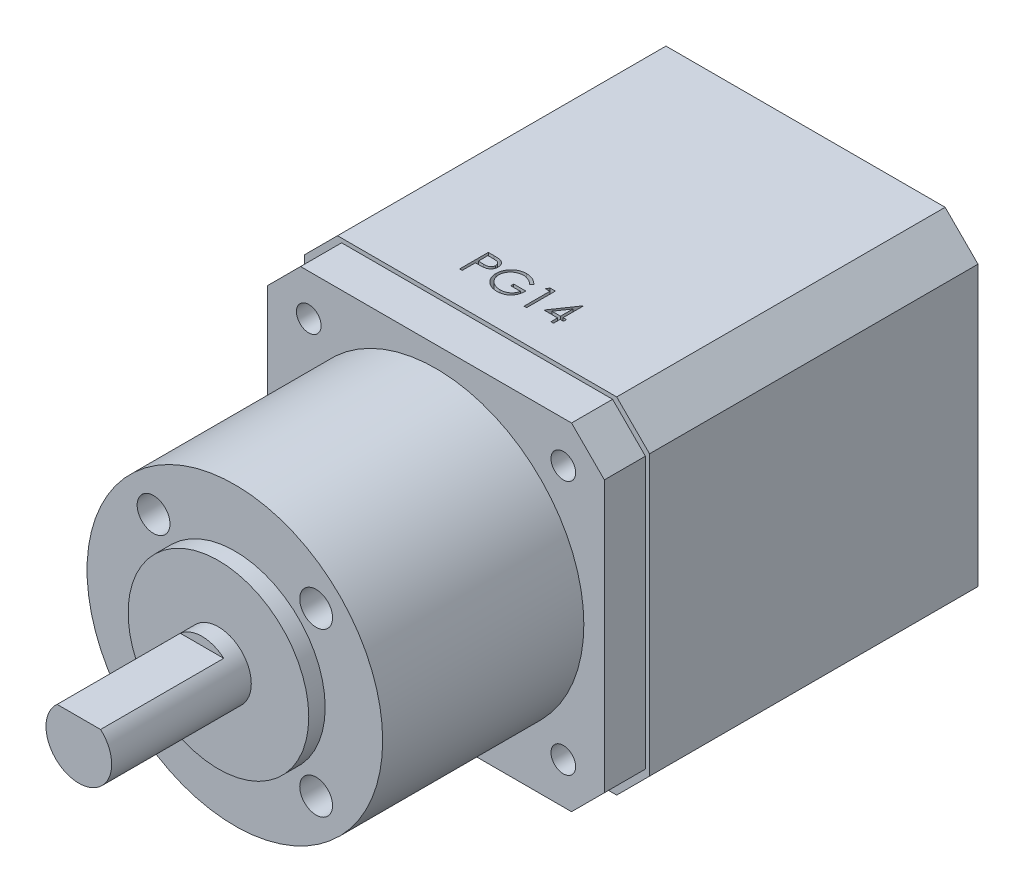
SolidWorks part; units mm, degrees
material "M1"
ref_plane "Front Plane" through (0, 0, 0) normal (0, 0, 1) x (1, 0, 0)
ref_plane "Top Plane" through (0, 0, 0) normal (0, 1, 0) x (1, 0, 0)
ref_plane "Right Plane" through (0, 0, 0) normal (1, 0, 0) x (0, 0, -1)
sketch "Sketch1" plane through (0, 0, 0) normal (0, 0, 1) x (1, 0, 0)
  line L1 (-21, -21) -> (21, -21)
  line L2 (-21, -21) -> (-21, 21)
  line L3 (-21, 21) -> (21, 21)
  line L4 (21, -21) -> (21, 21)
  line L5 (-21, -21) -> (21, 21) construction
  line L6 (-21, 21) -> (21, -21) construction
  point P0 (0, 0)
  dimension "D1" = 42
extrude "Boss-Extrude1" add sketch "Sketch1" along normal blind 40
sketch "Sketch2" plane through (0, 0, 40) normal (0, 0, 1) x (1, 0, 0)
  line L8 (20.5, -20.5) -> (20.5, 20.5)
  line L9 (20.5, 20.5) -> (-20.5, 20.5)
  line L10 (-20.5, 20.5) -> (-20.5, -20.5)
  line L11 (-20.5, -20.5) -> (20.5, -20.5)
  line L12 (20.5, -20.5) -> (20.5, 20.5)
  line L13 (20.5, 20.5) -> (-20.5, 20.5)
  line L14 (-20.5, 20.5) -> (-20.5, -20.5)
  line L15 (-20.5, -20.5) -> (20.5, -20.5)
  dimension "D1" = 0.5
extrude "Boss-Extrude2" add sketch "Sketch2" along normal blind 5
sketch "Sketch3" plane through (0, 0, 45) normal (0, 0, 1) x (1, 0, 0)
  circle A0 centre (0, 0) radius 18
  dimension "D1" = 36
extrude "Boss-Extrude3" add sketch "Sketch3" along normal blind 24.5
sketch "Sketch4" plane through (0, 0, 69.5) normal (0, 0, 1) x (1, 0, 0)
  circle A0 centre (0, 0) radius 11
  dimension "D1" = 22
extrude "Boss-Extrude4" add sketch "Sketch4" along normal blind 2
sketch "Sketch5" plane through (0, 0, 71.5) normal (0, 0, 1) x (1, 0, 0)
  circle A0 centre (0, 0) radius 4
  dimension "D1" = 8
extrude "Boss-Extrude5" add sketch "Sketch5" along normal blind 17
chamfer "Chamfer1" distance 4 angle 45 8 edges at (-21, 21, 20) (-20.5, 20.5, 42.5) (-21, -21, 20) (-20.5, -20.5, 42.5) (21, -21, 20) (20.5, -20.5, 42.5) (21, 21, 20) (20.5, 20.5, 42.5)
sketch "Sketch6" plane through (0, 0, 45) normal (0, 0, 1) x (1, 0, 0)
  line L1 (-15.5, -15.5) -> (15.5, -15.5) construction
  line L2 (-15.5, -15.5) -> (-15.5, 15.5) construction
  line L3 (-15.5, 15.5) -> (15.5, 15.5) construction
  line L4 (15.5, -15.5) -> (15.5, 15.5) construction
  line L5 (-15.5, -15.5) -> (15.5, 15.5) construction
  line L6 (-15.5, 15.5) -> (15.5, -15.5) construction
  circle A0 centre (15.5, 15.5) radius 1.5
  point P0 (0, 0)
  dimension "D2" = 3
  dimension "D1" = 31
extrude "Cut-Extrude1" cut sketch "Sketch6" against normal blind 8
pattern_circular "CirPattern1" count 4 over 360 about axis through (0, 0, 0) along (0, 0, 1) of "Cut-Extrude1"
sketch "Sketch7" plane through (0, 0, 69.5) normal (0, 0, 1) x (1, 0, 0)
  line L1 (-9.8995, -9.8995) -> (9.8995, -9.8995) construction
  line L2 (-9.8995, -9.8995) -> (-9.8995, 9.8995) construction
  line L3 (-9.8995, 9.8995) -> (9.8995, 9.8995) construction
  line L4 (9.8995, -9.8995) -> (9.8995, 9.8995) construction
  line L5 (-9.8995, -9.8995) -> (9.8995, 9.8995) construction
  line L6 (-9.8995, 9.8995) -> (9.8995, -9.8995) construction
  circle A0 centre (0, 0) radius 14 construction
  circle A1 centre (9.8995, 9.8995) radius 2
  dimension "D1" = 28
  dimension "D2" = 4
extrude "Cut-Extrude2" cut sketch "Sketch7" against normal blind 8
pattern_circular "CirPattern2" count 4 over 360 about axis through (0, 0, 0) along (0, 0, 1) of "Cut-Extrude2"
sketch "Sketch8" plane through (0, 0, 88.5) normal (0, 0, 1) x (1, 0, 0)
  line L0 (0, -4) -> (0, 3) construction
  line L1 (0, 3) -> (2.6458, 3) construction
  line L2 (2.6458, 3) -> (-2.6458, 3)
  circle A0 centre (0, 0) radius 4 construction
  circle A1 centre (0, 0) radius 4 construction
  arc A2 (-2.6458, 3) -> (2.6458, 3) centre (0, 0) cw
  dimension "D1" = 7
extrude "Cut-Extrude3" cut sketch "Sketch8" against normal offset from surface (15 mm away) 2 up to face at (4, 0, 71.5)
sketch "Sketch9" plane through (0, 21, 0) normal (0, 1, 0) x (1, 0, 0)
  text T0 "PG14"
extrude "Cut-Extrude4" cut sketch "Sketch9" against normal blind 10
